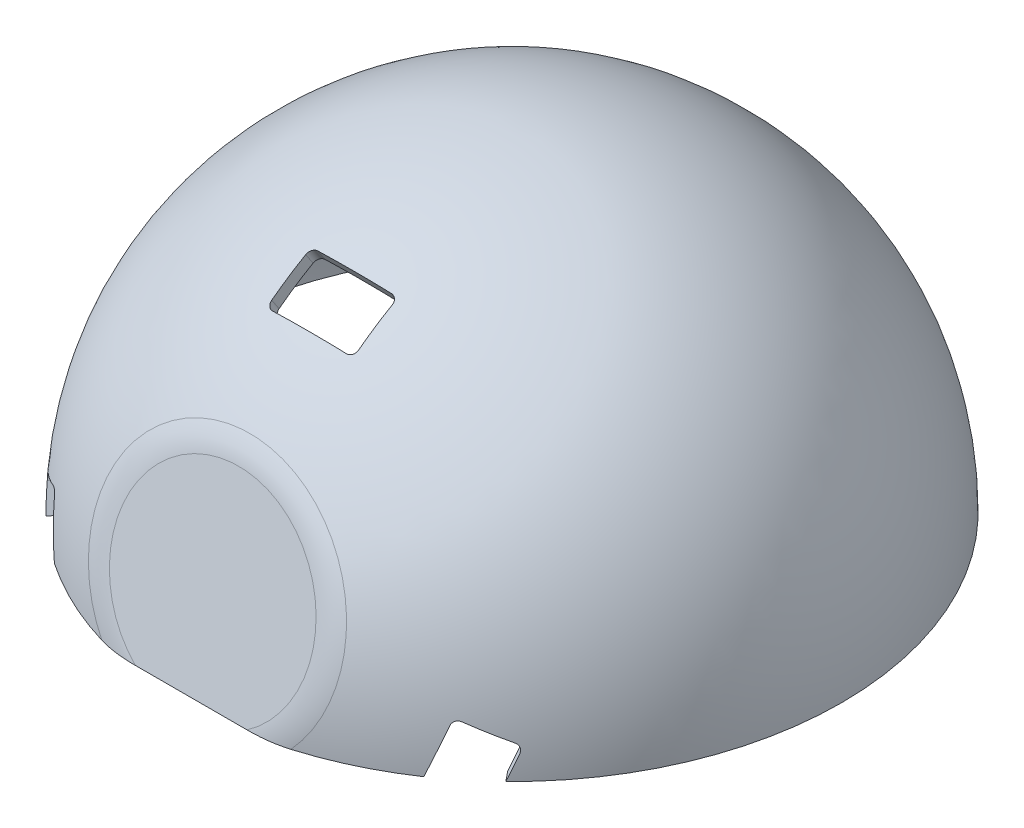
SolidWorks part; units mm, degrees
ref_plane "Plan de face" through (0, 0, 0) normal (0, 0, 1) x (1, 0, 0)
ref_plane "Plan de dessus" through (0, 0, 0) normal (0, 1, 0) x (1, 0, 0)
ref_plane "Plan de droite" through (0, 0, 0) normal (1, 0, 0) x (0, 0, -1)
sketch "Esquisse1" plane through (0, 0, 0) normal (0, 0, 1) x (1, 0, 0)
  line L0 (0, 0) -> (0, 50.175) construction
  line L1 (0, 0) -> (50.175, 0) construction
  line L2 (50.175, 0) -> (50.175, 50.6582) construction
  line L3 (0, 50.175) -> (34.9819, 50.175) construction
  arc A0 (50.175, 0) -> (0, 50.175) centre (0, 0) ccw
  point P0 (-0.7172, 50.175)
  dimension "D1" = 100.35
revolve "Révol.-Mince1" add sketch "Esquisse1" angle 360 about L0 wall 2
sketch "Esquisse3" plane through (0, 0, 0) normal (0, 1, 0) x (1, 0, 0)
  line L0 (0, 0) -> (42.2522, 0) construction
ref_plane "Plan4" through (0, 0, 0) normal (0, 0.2588, 0.9659) x (1, 0, 0)
ref_plane "Plan6" through (0, 12.9862, 48.4653) normal (0, 0.2588, 0.9659) x (1, 0, 0)
ref_plane "Plan1" through (0, 0, 0) normal (0, 0.8339, 0.5519) x (1, 0, 0)
sketch "Esquisse4" plane through (0, 0, 0) normal (0, 0.8339, 0.5519) x (1, 0, 0)
  line L1 (-5.6, 4.1) -> (5.6, 4.1)
  line L2 (-6.6, 3.1) -> (-6.6, -3.1)
  line L3 (-5.6, -4.1) -> (5.6, -4.1)
  line L4 (6.6, 3.1) -> (6.6, -3.1)
  line L5 (-6.6, 4.1) -> (6.6, -4.1) construction
  line L6 (-6.6, -4.1) -> (6.6, 4.1) construction
  arc A0 (6.6, 3.1) -> (5.6, 4.1) centre (5.6, 3.1) ccw
  arc A1 (5.6, -4.1) -> (6.6, -3.1) centre (5.6, -3.1) ccw
  arc A2 (-6.6, -3.1) -> (-5.6, -4.1) centre (-5.6, -3.1) ccw
  arc A3 (-5.6, 4.1) -> (-6.6, 3.1) centre (-5.6, 3.1) ccw
  point P0 (0, 0)
  dimension "D4" = 1
  dimension "D5" = 1
  dimension "D6" = 1
  dimension "D7" = 1
  dimension "D1" = 13.2
  dimension "D2" = 8.2
  dimension "D3" = 0
extrude "Enlèv. mat.-Extru.2" cut sketch "Esquisse4" along normal through all
sketch "Esquisse5" plane through (0, 0, 0) normal (1, 0, 0) x (0, 0, -1)
  line L0 (0, 0) -> (0, 39.4205) construction
ref_plane "Plan2" through (0, 0, 0) normal (0.6315, 0, 0.7754) x (0, 1, 0)
sketch "Esquisse6" plane through (0, 0, 0) normal (0.6315, 0, 0.7754) x (0, 1, 0)
  line L0 (0, 0) -> (39.4205, 0) construction
  line L1 (6.7427, 1.6449) -> (-3.6047, 5.9309)
  line L2 (7.2839, 0.3383) -> (4.9113, -5.3897)
  line L3 (3.6047, -5.9309) -> (-6.7427, -1.6449)
  line L4 (-4.9113, 5.3897) -> (-7.2839, -0.3383)
  line L5 (7.6666, 1.2622) -> (-7.6666, -1.2622) construction
  line L6 (4.5286, -6.3136) -> (-4.5286, 6.3136) construction
  line L7 (0, 0) -> (0, 19.8431) construction
  arc A0 (6.7427, 1.6449) -> (7.2839, 0.3383) centre (6.36, 0.721) cw
  arc A1 (-4.9113, 5.3897) -> (-3.6047, 5.9309) centre (-3.9874, 5.0071) cw
  arc A2 (-6.7427, -1.6449) -> (-7.2839, -0.3383) centre (-6.36, -0.721) cw
  arc A3 (4.9113, -5.3897) -> (3.6047, -5.9309) centre (3.9874, -5.0071) cw
  point P0 (0, 0)
  dimension "D4" = 1
  dimension "D5" = 1
  dimension "D6" = 1
  dimension "D3" = 1
  dimension "D1" = 8.2
  dimension "D2" = 13.2
  dimension "D7" = 22.5
extrude "Enlèv. mat.-Extru.3" cut sketch "Esquisse6" along normal through all
ref_plane "Plan3" through (0, 0, 0) normal (-0.6315, 0, 0.7754) x (0, 1, 0)
sketch "Esquisse7" plane through (0, 0, 0) normal (-0.6315, 0, 0.7754) x (0, 1, 0)
  line L0 (0, 0) -> (0, 8.4978) construction
  line L1 (-6.7427, 1.6449) -> (3.6047, 5.9309)
  line L2 (-7.2839, 0.3383) -> (-4.9113, -5.3897)
  line L3 (-3.6047, -5.9309) -> (6.7427, -1.6449)
  line L4 (4.9113, 5.3897) -> (7.2839, -0.3383)
  line L5 (-7.6666, 1.2622) -> (7.6666, -1.2622) construction
  line L6 (-4.5286, -6.3136) -> (4.5286, 6.3136) construction
  line L8 (0, 50.175) -> (0, -50.175) construction
  arc A0 (-6.7427, 1.6449) -> (-7.2839, 0.3383) centre (-6.36, 0.721) ccw
  arc A1 (4.9113, 5.3897) -> (3.6047, 5.9309) centre (3.9874, 5.0071) ccw
  arc A2 (6.7427, -1.6449) -> (7.2839, -0.3383) centre (6.36, -0.721) ccw
  arc A3 (-4.9113, -5.3897) -> (-3.6047, -5.9309) centre (-3.9874, -5.0071) ccw
  point P0 (0, 0)
  dimension "D4" = 1
  dimension "D5" = 1
  dimension "D6" = 1
  dimension "D1" = 13.2
  dimension "D2" = 8.2
  dimension "D3" = 1
  dimension "D7" = 22.5
extrude "Enlèv. mat.-Extru.4" cut sketch "Esquisse7" along normal through all
ref_plane "Plan5" through (0, 0, 0) normal (0, -0.9659, 0.2588) x (1, 0, 0)
sketch "Esquisse9" plane through (0, 12.9862, 48.4653) normal (0, 0.2588, 0.9659) x (1, 0, 0)
  circle A0 centre (0, 0) radius 50.1026
extrude "Enlèv. mat.-Extru.5" cut sketch "Esquisse9" against normal blind 3
sketch "Esquisse10" plane through (0, 12.2098, 45.5676) normal (0, 0.2588, 0.9659) x (1, 0, 0)
  line L2 (-11.5008, -12.6405) -> (11.5008, -12.6405)
  line L4 (-11.5008, -12.6405) -> (11.5008, -12.6405)
  arc A3 (11.5008, -12.6405) -> (-11.5008, -12.6405) centre (0, 0) ccw
  arc A5 (11.5008, -12.6405) -> (-11.5008, -12.6405) centre (0, 0) ccw
  dimension "D1" = 0
extrude "Boss.-Extru.1" add sketch "Esquisse10" against normal blind 2
fillet "Congé1" radius 10 2 edges at (0, 27.8566, 39.3044) (0, 28.7169, 41.1445)
sketch "Esquisse11" plane through (0, 0, 0) normal (0, 1, 0) x (1, 0, 0)
  circle A0 centre (0, 0) radius 61.0559
extrude "Enlèv. mat.-Extru.6" cut sketch "Esquisse11" against normal blind 10
equation "\"l_pieds\"=13.2"
equation "\"D1@Esquisse4\"=\"l_pieds\""
equation "\"h_pieds\"=8.2"
equation "\"D2@Esquisse4\"=\"h_pieds\""
equation "\"D2@Esquisse6\"=\"l_pieds\""
equation "\"D1@Esquisse6\"=\"h_pieds\""
equation "\"D1@Esquisse7\"=\"l_pieds\""
equation "\"D2@Esquisse7\"=\"h_pieds\""
